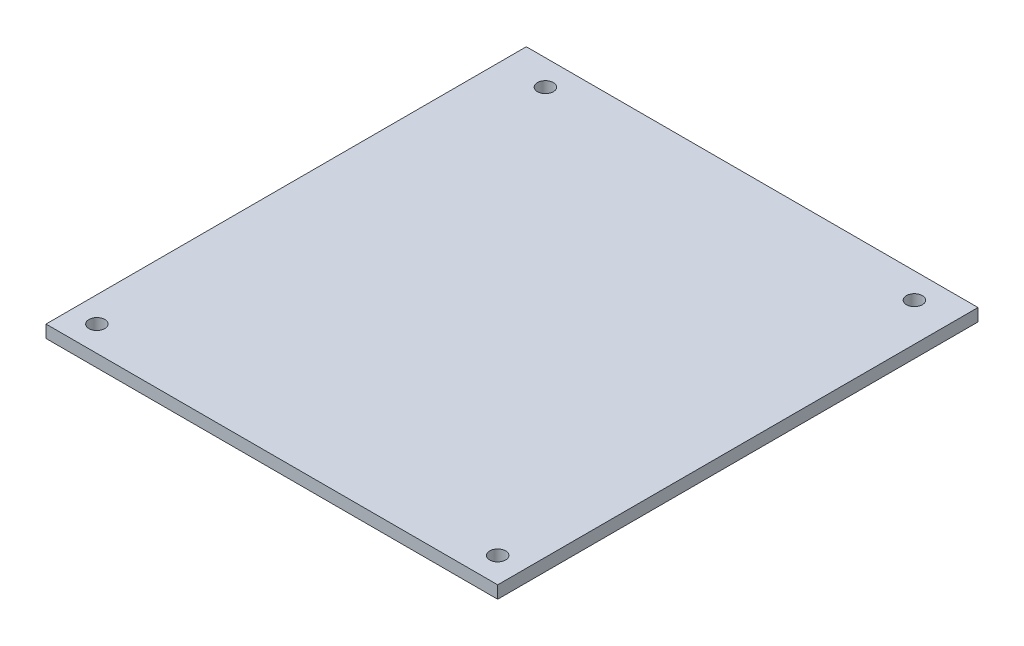
SolidWorks part; units mm, degrees
ref_plane "Front" through (0, 0, 0) normal (0, 0, 1) x (1, 0, 0)
ref_plane "Top" through (0, 0, 0) normal (0, 1, 0) x (1, 0, 0)
ref_plane "Right" through (0, 0, 0) normal (1, 0, 0) x (0, 0, -1)
sketch "Sketch1" plane through (0, 0, 0) normal (0, 1, 0) x (1, 0, 0)
  line L1 (-45.085, -47.9425) -> (45.085, -47.9425)
  line L2 (-45.085, -47.9425) -> (-45.085, 47.9425)
  line L3 (-45.085, 47.9425) -> (45.085, 47.9425)
  line L4 (45.085, -47.9425) -> (45.085, 47.9425)
  line L5 (-45.085, -47.9425) -> (45.085, 47.9425) construction
  line L6 (-45.085, 47.9425) -> (45.085, -47.9425) construction
  point P0 (0, 0)
  dimension "D1" = 95.885
  dimension "D2" = 90.17
extrude "Boss-Extrude1" add sketch "Sketch1" along normal blind 2.5
sketch "Sketch2" plane through (0, 2.5, 0) normal (0, 1, 0) x (1, 0, 0)
  line L0 (-45.085, 47.9425) -> (-45.085, -47.9425) construction
  line L1 (-45.085, -47.9425) -> (45.085, -47.9425) construction
  circle A0 centre (-40.005, -42.8625) radius 1.5875
  circle A1 centre (-36.195, 42.8625) radius 1.5875
  circle A2 centre (37.465, 42.8625) radius 1.5875
  circle A3 centre (40.005, -42.8625) radius 1.5875
  dimension "D1" = 3.175
  dimension "D2" = 5.08
  dimension "D3" = 5.08
  dimension "D4" = 80.01
  dimension "D5" = 85.725
  dimension "D6" = 3.81
  dimension "D7" = 73.66
extrude "Cut-Extrude1" cut sketch "Sketch2" against normal blind 2.5
